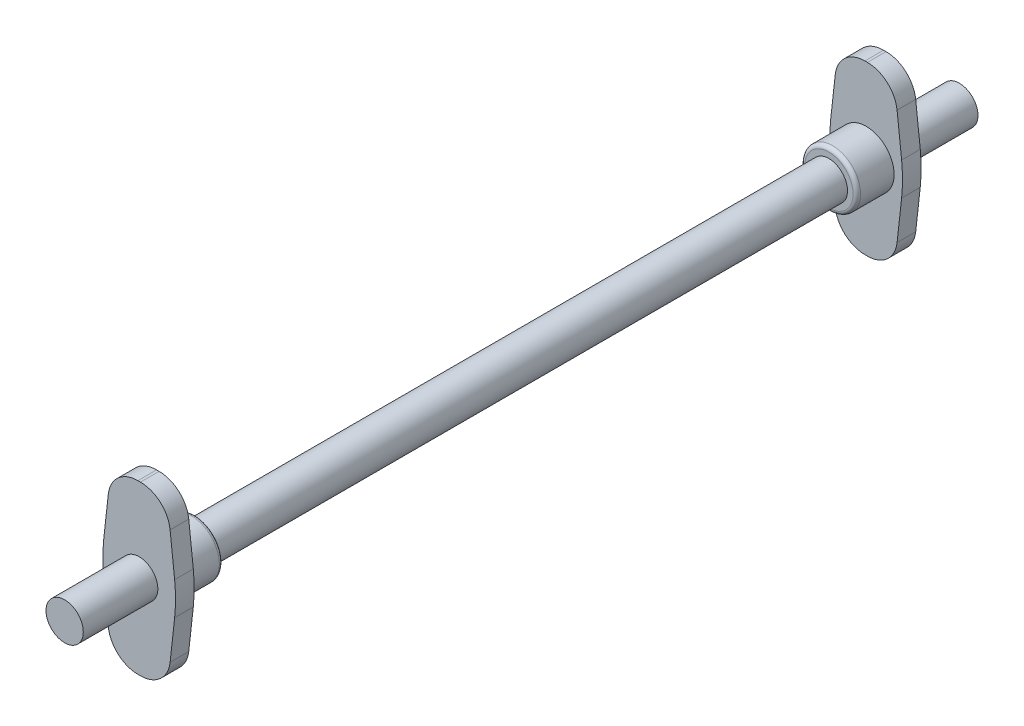
SolidWorks part; units mm, degrees
ref_plane "Front Plane" through (0, 0, 0) normal (0, 0, 1) x (1, 0, 0)
ref_plane "Top Plane" through (0, 0, 0) normal (0, 1, 0) x (1, 0, 0)
ref_plane "Right Plane" through (0, 0, 0) normal (1, 0, 0) x (0, 0, -1)
sketch "Sketch1" plane through (0, 0, 0) normal (0, 0, 1) x (1, 0, 0)
  circle A0 centre (0, 0) radius 3.175
  dimension "D1" = 6.35
extrude "Boss-Extrude1" add sketch "Sketch1" along normal blind 53.975
sketch "Sketch2" plane through (0, 0, 53.975) normal (0, 0, 1) x (1, 0, 0)
  circle A0 centre (0, 0) radius 4.7625
  dimension "D1" = 9.525
extrude "Boss-Extrude2" add sketch "Sketch2" along normal blind 6.35
sketch "Sketch3" plane through (0, 0, 60.325) normal (0, 0, 1) x (1, 0, 0)
  line L0 (-0.2157, 14.2875) -> (0.2157, 14.2875)
  line L5 (5.2646, 9.7685) -> (6.0383, 2.805)
  line L6 (6.0383, -2.805) -> (5.2646, -9.7685)
  line L7 (4.7625, 14.2875) -> (-4.7625, 14.2875) construction
  line L9 (4.7625, -14.2875) -> (-4.7625, -14.2875) construction
  line L11 (0.2157, -14.2875) -> (-0.2157, -14.2875)
  line L12 (-5.2646, -9.7685) -> (-6.0383, -2.805)
  line L13 (-6.35, 0) -> (-4.7625, 14.2875) construction
  line L14 (-6.35, 0) -> (-4.7625, -14.2875) construction
  line L15 (4.7625, -14.2875) -> (6.35, 0) construction
  line L16 (6.35, 0) -> (4.7625, 14.2875) construction
  line L17 (-6.0383, 2.805) -> (-5.2646, 9.7685)
  arc A0 (-0.2157, -14.2875) -> (-5.2646, -9.7685) centre (-0.2157, -9.2075) cw
  arc A1 (5.2646, -9.7685) -> (0.2157, -14.2875) centre (0.2157, -9.2075) cw
  arc A2 (0.2157, 14.2875) -> (5.2646, 9.7685) centre (0.2157, 9.2075) cw
  arc A3 (-0.2157, 14.2875) -> (-5.2646, 9.7685) centre (-0.2157, 9.2075) ccw
  arc A4 (6.0383, 2.805) -> (6.0383, -2.805) centre (-19.2063, 0) cw
  arc A5 (-6.0383, -2.805) -> (-6.0383, 2.805) centre (19.2063, 0) cw
  point P0 (0, 0)
  point P6 (0, 0)
  dimension "D1" = 5.08
  dimension "D2" = 25.4
extrude "Boss-Extrude3" add sketch "Sketch3" along normal blind 3.175
mirror "Mirror1" about plane through (0, 0, 0) normal (0, 0, 1) of "Boss-Extrude3", "Boss-Extrude2", "Boss-Extrude1"
fillet "Fillet1" radius 0.635 2 edges at (4.7625, 0, 53.975) (4.7625, 0, -53.975)
sketch "Sketch4" plane through (0, 0, 63.5) normal (0, 0, 1) x (1, 0, 0)
  circle A0 centre (0, 0) radius 3.175
  dimension "D1" = 6.35
extrude "Boss-Extrude4" add sketch "Sketch4" along normal blind 12.7
mirror "Mirror2" about plane through (0, 0, 0) normal (0, 0, 1) of "Boss-Extrude4"
